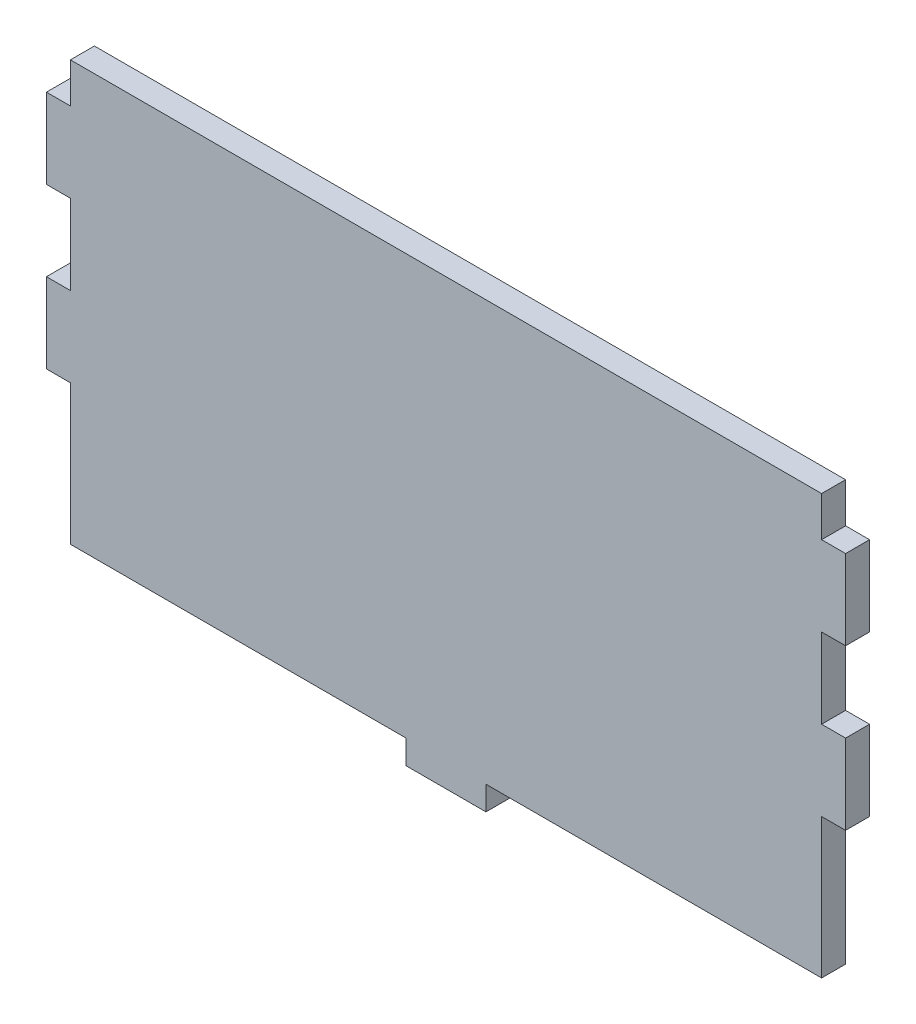
SolidWorks part; units mm, degrees
ref_plane "前基準面" through (0, 0, 0) normal (0, 0, 1) x (1, 0, 0)
ref_plane "上基準面" through (0, 0, 0) normal (0, 1, 0) x (1, 0, 0)
ref_plane "右基準面" through (0, 0, 0) normal (1, 0, 0) x (0, 0, -1)
sketch "草圖1" plane through (0, 0, 0) normal (0, 0, 1) x (1, 0, 0)
  line L0 (0, -27.2342) -> (0, -34.9328) construction
  line L1 (-47, 25.2658) -> (47, 25.2658)
  line L2 (-47, 25.2658) -> (-47, -27.2342)
  line L3 (-47, -27.2342) -> (47, -27.2342)
  line L4 (47, 25.2658) -> (47, -27.2342)
  line L5 (-47, 10.2658) -> (-50, 10.2658)
  line L6 (-47, 10.2658) -> (-47, 20.2658)
  line L7 (-47, 0.2658) -> (-50, 0.2658)
  line L8 (-47, 0.2658) -> (-47, -9.7342)
  line L9 (-47, -9.7342) -> (-50, -9.7342)
  line L10 (-50, 0.2658) -> (-50, -9.7342)
  line L11 (-47, 20.2658) -> (-50, 20.2658)
  line L12 (-50, 10.2658) -> (-50, 20.2658)
  line L13 (0, -27.2342) -> (0, 25.2658) construction
  line L14 (-5, -27.2342) -> (5, -27.2342)
  line L15 (-5, -27.2342) -> (-5, -30.2342)
  line L16 (-5, -30.2342) -> (5, -30.2342)
  line L17 (5, -27.2342) -> (5, -30.2342)
  line L18 (47, -9.7342) -> (50, -9.7342)
  line L19 (50, 0.2658) -> (50, -9.7342)
  line L20 (47, 0.2658) -> (50, 0.2658)
  line L21 (47, 0.2658) -> (47, -9.7342)
  line L22 (47, 20.2658) -> (50, 20.2658)
  line L23 (50, 10.2658) -> (50, 20.2658)
  line L24 (47, 10.2658) -> (50, 10.2658)
  line L25 (47, 10.2658) -> (47, 20.2658)
  point P0 (0, 0)
  point P14 (-48.5, 0.2658)
  point P21 (0, -30.2342)
  dimension "D1" = 94
  dimension "D2" = 3
  dimension "D3" = 10
  dimension "D4" = 17.5
  dimension "D5" = 10
  dimension "D6" = 3
  dimension "D7" = 10
  dimension "D8" = 5
  dimension "D9" = 3
  dimension "D10" = 10
extrude "填料-伸長1" add sketch "草圖1" along normal blind 3 contours L7 L10 L9 L2 | L4 L1 L2 L3 L14 | L0 L3 L15 L16 | L14 L0 L16 L17 | L12 L11 L6 L5 | L22 L23 L24 L25 | L18 L19 L20 L21
